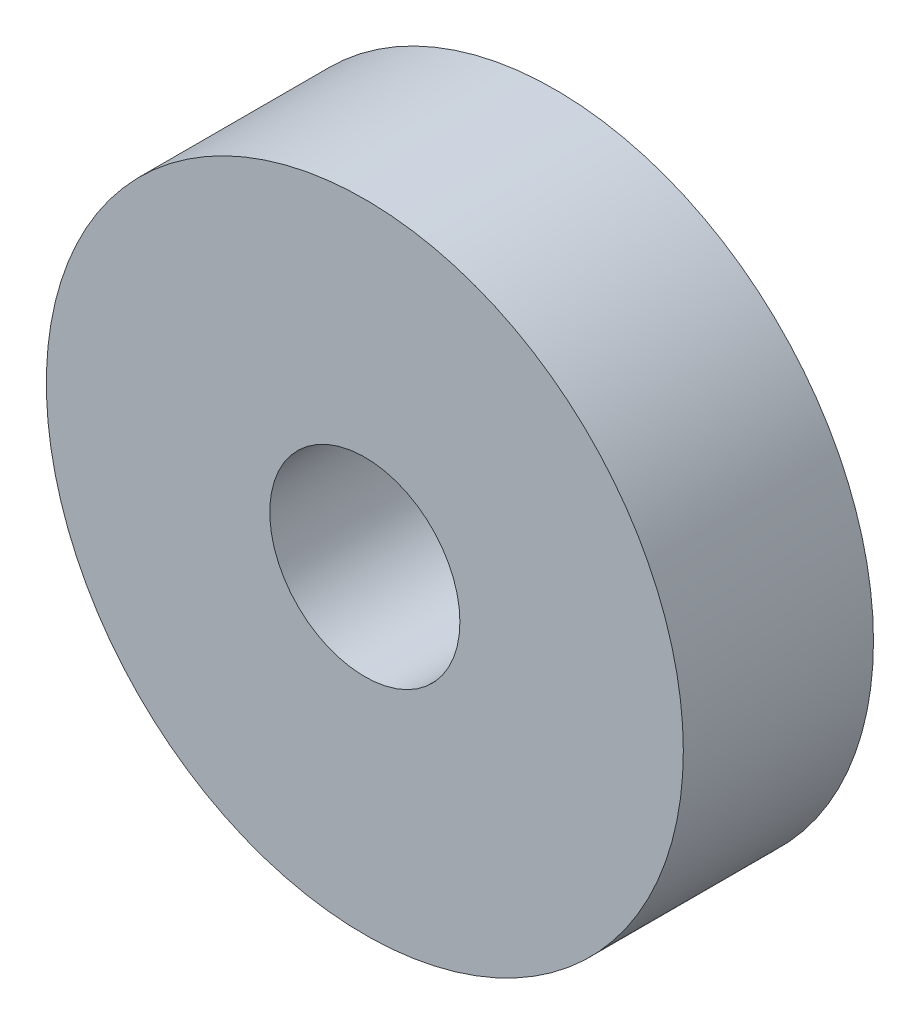
SolidWorks part; units mm, degrees
ref_plane "Front Plane" through (0, 0, 0) normal (0, 0, 1) x (1, 0, 0)
ref_plane "Top Plane" through (0, 0, 0) normal (0, 1, 0) x (1, 0, 0)
ref_plane "Right Plane" through (0, 0, 0) normal (1, 0, 0) x (0, 0, -1)
sketch "Sketch1" plane through (0, 0, 0) normal (0, 0, 1) x (1, 0, 0)
  circle A0 centre (0.5774, 0.0962) radius 3
  circle A1 centre (0.5774, 0.0962) radius 10.0499
extrude "Boss-Extrude1" add sketch "Sketch1" along normal blind 6
